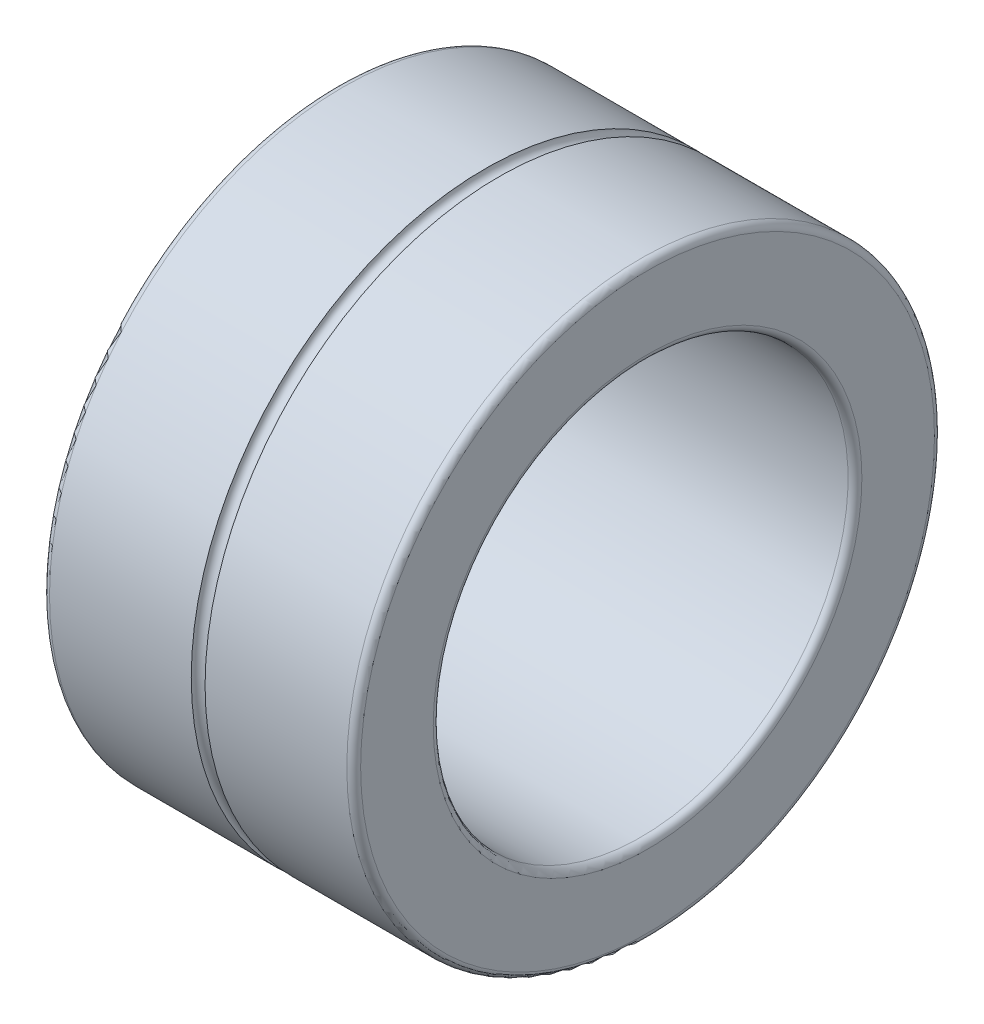
SolidWorks part; units mm, degrees
ref_plane "Front Plane" through (0, 0, 0) normal (0, 0, 1) x (1, 0, 0)
ref_plane "Top Plane" through (0, 0, 0) normal (0, 1, 0) x (1, 0, 0)
ref_plane "Right Plane" through (0, 0, 0) normal (1, 0, 0) x (0, 0, -1)
sketch "Sketch1" plane through (0, 0, 0) normal (0, 0, 1) x (1, 0, 0)
  line L0 (0, 30) -> (0, 42.5)
  line L1 (0, 42.5) -> (21.5, 42.5)
  line L2 (23.5, 42.5) -> (45, 42.5)
  line L3 (45, 42.5) -> (45, 30)
  line L4 (45, 30) -> (0, 30)
  line L5 (0, 0) -> (76.4062, 0) construction
  line L6 (22.5, 42.5) -> (22.5, 30) construction
  arc A1 (21.5, 42.5) -> (23.5, 42.5) centre (22.5, 42.5) ccw
  point P1 (22.5, 30)
  dimension "D4" = 1
  dimension "D1" = 60
  dimension "D2" = 85
  dimension "D3" = 45
revolve "Revolve1" add sketch "Sketch1" angle 360 about L5
fillet "Fillet1" radius 1 4 edges at (0, 0, 30) (0, 0, 42.5) (45, 0, 42.5) (45, 0, 30)
